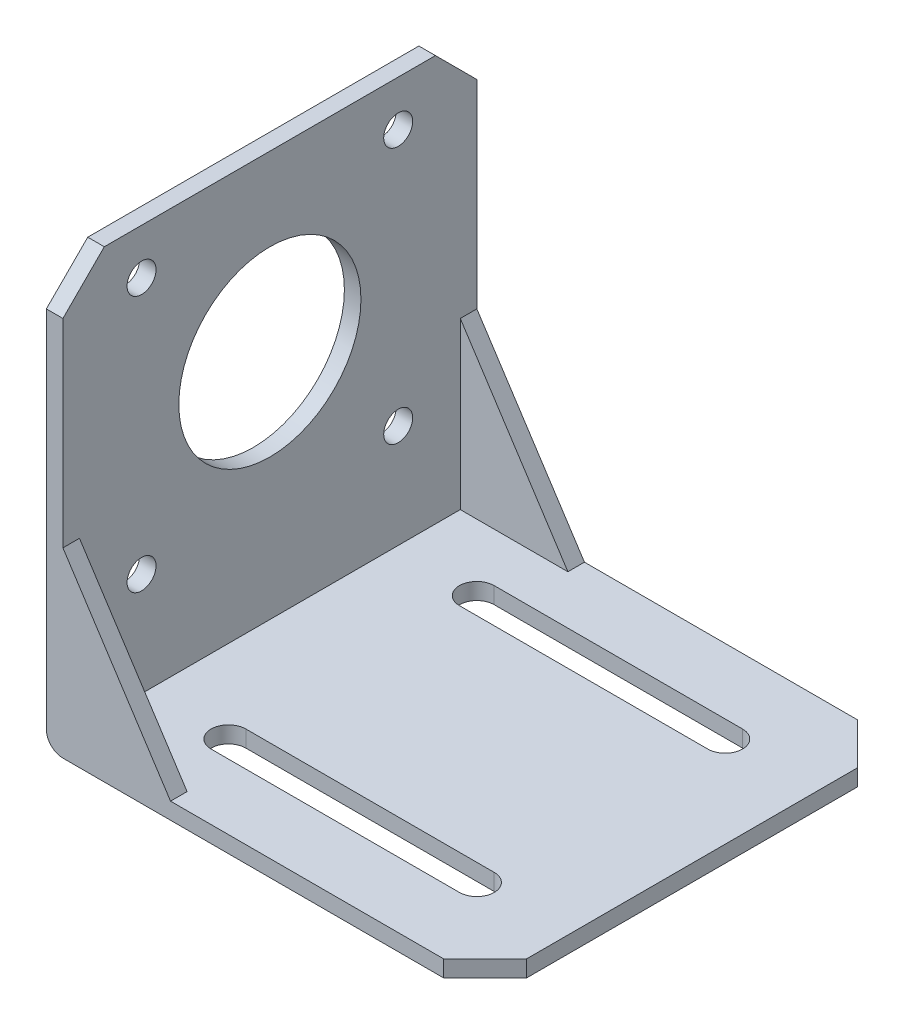
SolidWorks part; units mm, degrees
ref_plane "前视基准面" through (0, 0, 0) normal (0, 0, 1) x (1, 0, 0)
ref_plane "上视基准面" through (0, 0, 0) normal (0, 1, 0) x (1, 0, 0)
ref_plane "右视基准面" through (0, 0, 0) normal (1, 0, 0) x (0, 0, -1)
other "Configuration Table"
sketch "草图1" plane through (0, 0, 0) normal (0, 1, 0) x (1, 0, 0)
  line L4 (0, 0) -> (53, 0) construction
  line L5 (0, 0) -> (0, 25)
  line L6 (0, 25) -> (48, 25)
  line L7 (48, 25) -> (53, 20)
  line L8 (53, 20) -> (53, 0)
  line L9 (12, 15) -> (42, 15) construction
  line L10 (12, 17.1) -> (42, 17.1)
  line L11 (12, 12.9) -> (42, 12.9)
  line L12 (0, 0) -> (53, 0)
  arc A0 (12, 17.1) -> (12, 12.9) centre (12, 15) ccw
  arc A1 (42, 12.9) -> (42, 17.1) centre (42, 15) ccw
  point P8 (27, 15)
  dimension "D1" = 50
  dimension "D2" = 30
  dimension "D3" = 30
  dimension "D4" = 4.2
  dimension "D5" = 11
  dimension "D6" = 5
  dimension "D7" = 45
  dimension "D8" = 53
extrude "凸台-拉伸1" add sketch "草图1" along normal blind 2
sketch "草图2" plane through (0, 0, 0) normal (-1, 0, 0) x (0, 0, 1)
  line L0 (0, 2) -> (0, 39.7141) construction
  line L1 (-25, 2) -> (-25, 46)
  line L2 (-25, 46) -> (-20, 51)
  line L3 (-20, 51) -> (0, 51)
  line L4 (-10.9103, 30) -> (12.4076, 30) construction
  line L5 (-25, 2) -> (0, 2) construction
  line L6 (-15.5, 60.9135) -> (-15.5, -2.4179) construction
  line L7 (0, 51) -> (0, 2)
  line L8 (0, 2) -> (-25, 2)
  circle A0 centre (0, 30) radius 11
  circle A1 centre (-15.5, 14.5) radius 1.75
  circle A2 centre (-15.5, 45.5) radius 1.75
  line M14 (0, 2) -> (-25, 2)
  dimension "D3" = 3.5
  dimension "D8" = 22
  dimension "D1" = 21
  dimension "D2" = 49
  dimension "D4" = 31
  dimension "D5" = 15.5
  dimension "D6" = 45
  dimension "D7" = 5
extrude "凸台-拉伸2" add sketch "草图2" against normal blind 2 contours A0 L7 L3 L2 L1 A2 A1 M14
mirror "镜向2" about plane through (0, 0, 0) normal (0, 0, 1) of "凸台-拉伸1", "凸台-拉伸2"
fillet "圆角1" radius 2 1 edges at (0, 0, 0)
sketch "草图4" plane through (0, 0, 25) normal (0, 0, 1) x (1, 0, 0)
  line L0 (2, 2) -> (2, 22)
  line L1 (2, 2) -> (2, 46) construction
  line L2 (2, 22) -> (15, 2)
  line L3 (48, 2) -> (2, 2) construction
  line L4 (15, 2) -> (2, 2)
  dimension "D1" = 13
  dimension "D2" = 20
extrude "凸台-拉伸3" add sketch "草图4" against normal blind 2
mirror "镜向4" about plane through (0, 0, 0) normal (0, 0, 1) of "凸台-拉伸3"
